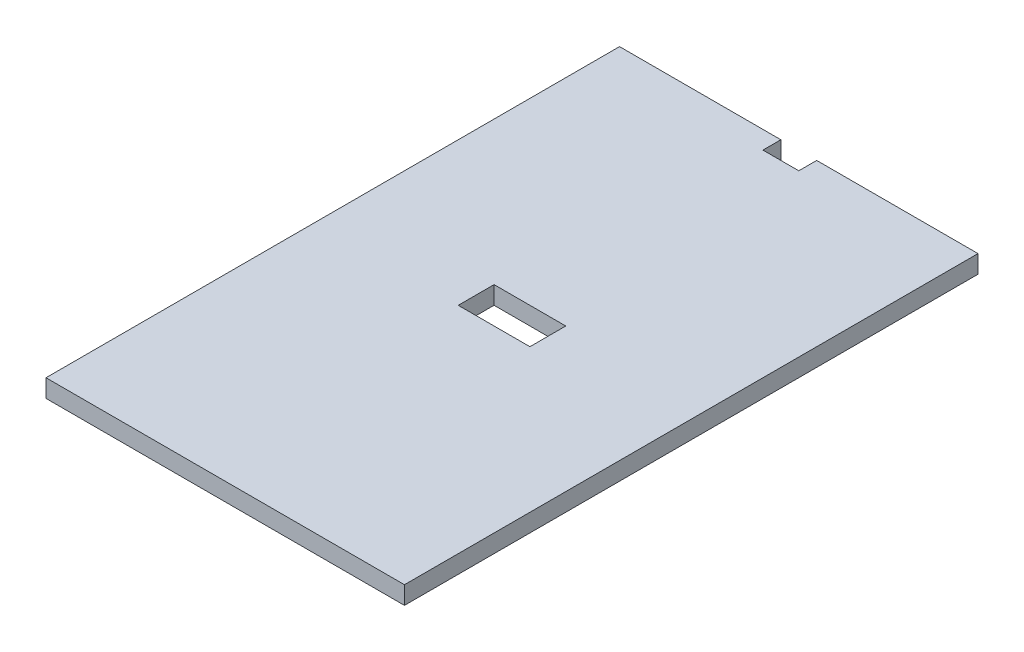
SolidWorks part; units mm, degrees
ref_plane "Ebene vorne" through (0, 0, 0) normal (0, 0, 1) x (1, 0, 0)
ref_plane "Ebene oben" through (0, 0, 0) normal (0, 1, 0) x (1, 0, 0)
ref_plane "Ebene rechts" through (0, 0, 0) normal (1, 0, 0) x (0, 0, -1)
sketch "Skizze1" plane through (0, 0, 0) normal (0, 1, 0) x (1, 0, 0)
  line L1 (50, 80) -> (-50, 80)
  line L2 (50, 80) -> (50, -80)
  line L3 (50, -80) -> (-50, -80)
  line L4 (-50, 80) -> (-50, -80)
  line L5 (50, 80) -> (-50, -80) construction
  line L6 (50, -80) -> (-50, 80) construction
  line L7 (-10, -5) -> (10, -5)
  line L8 (-10, -5) -> (-10, 5)
  line L9 (-10, 5) -> (10, 5)
  line L10 (10, -5) -> (10, 5)
  line L11 (-10, -5) -> (10, 5) construction
  line L12 (-10, 5) -> (10, -5) construction
  point P0 (0, 0)
  point P6 (0, 0)
  dimension "D1" = 100
  dimension "D2" = 160
  dimension "D3" = 20
  dimension "D4" = 10
extrude "Aufsatz-Linear austragen1" add sketch "Skizze1" along normal blind 5
sketch "Skizze2" plane through (0, 5, 0) normal (0, 1, 0) x (1, 0, 0)
  line L0 (0, 80) -> (0, -49920) construction
  line L1 (50, 80) -> (-50, 80) construction
  line L3 (-5, 80) -> (5, 80)
  line L4 (-5, 80) -> (-5, 75)
  line L5 (-5, 75) -> (5, 75)
  line L6 (5, 80) -> (5, 75)
  point P4 (0, 80)
  dimension "D1" = 10
  dimension "D2" = 5
extrude "Schnitt-Linear austragen1" cut sketch "Skizze2" against normal through all
